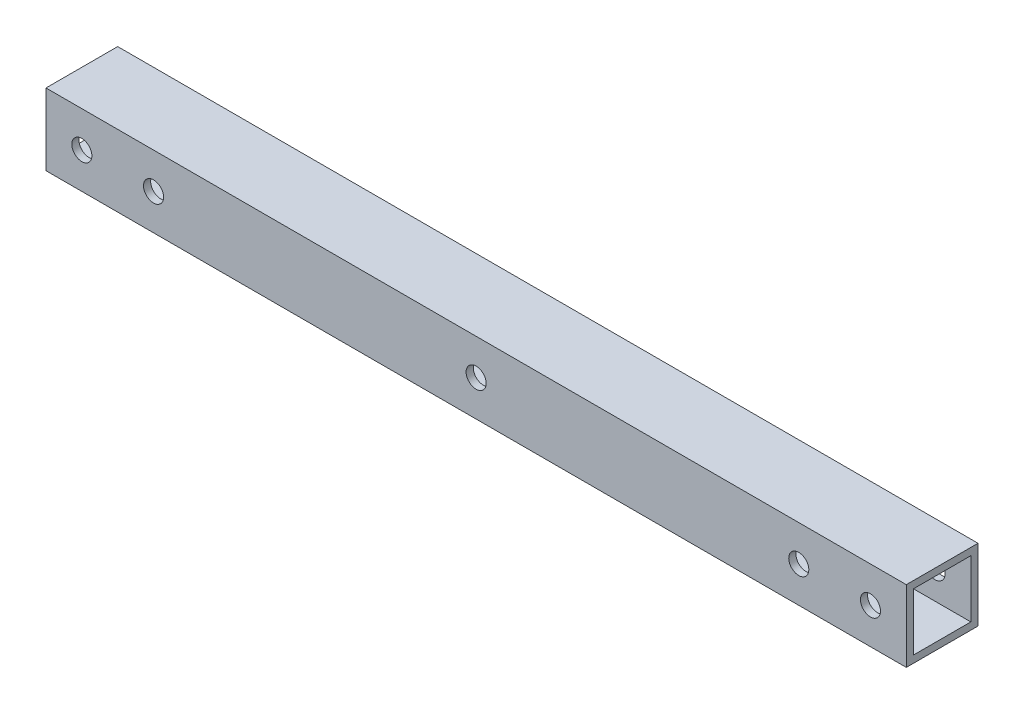
SolidWorks part; units mm, degrees
material "5052-H34"
ref_plane "正面" through (0, 0, 0) normal (0, 0, 1) x (1, 0, 0)
ref_plane "平面" through (0, 0, 0) normal (0, 1, 0) x (1, 0, 0)
ref_plane "右側面" through (0, 0, 0) normal (1, 0, 0) x (0, 0, -1)
sketch "ｽｹｯﾁ1" plane through (0, 0, 0) normal (1, 0, 0) x (0, 0, -1)
  line L1 (-7.5, 7.5) -> (7.5, 7.5)
  line L2 (-7.5, 7.5) -> (-7.5, -7.5)
  line L3 (-7.5, -7.5) -> (7.5, -7.5)
  line L4 (7.5, 7.5) -> (7.5, -7.5)
  line L5 (-7.5, 7.5) -> (7.5, -7.5) construction
  line L6 (-7.5, -7.5) -> (7.5, 7.5) construction
  point P0 (0, 0)
  dimension "D1" = 15
extrude "押し出し-薄板1" add sketch "ｽｹｯﾁ1" along normal blind 180 thin
sketch "ｽｹｯﾁ2" plane through (0, 0, 7.5) normal (0, 0, 1) x (1, 0, 0)
  line L0 (90, 7.5) -> (90, -7.5) construction
  line L1 (180, 7.5) -> (0, 7.5) construction
  line L2 (180, -7.5) -> (0, -7.5) construction
  line L3 (0, 0) -> (22.5, 0) construction
  line L4 (0, 7.5) -> (0, -7.5) construction
  line L5 (180, 0) -> (157.5, 0) construction
  circle A0 centre (22.5, 0) radius 2.1
  circle A1 centre (7.5, 0) radius 2.1
  circle A2 centre (172.5, 0) radius 2.1
  circle A3 centre (157.5, 0) radius 2.1
  circle A4 centre (90, 0) radius 2.1
  dimension "D1" = 4.2
  dimension "D2" = 7.5
  dimension "D3" = 15
extrude "ｶｯﾄ - 押し出し1" cut sketch "ｽｹｯﾁ2" against normal through all
